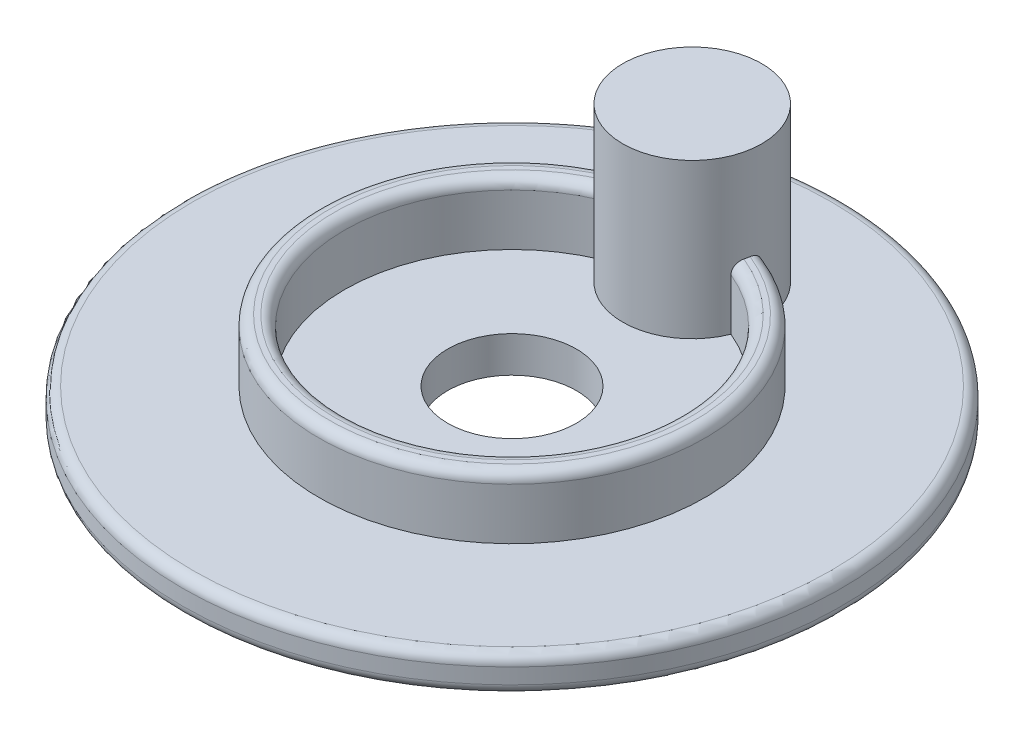
SolidWorks part; units mm, degrees
ref_plane "Front Plane" through (0, 0, 0) normal (0, 0, 1) x (1, 0, 0)
ref_plane "Top Plane" through (0, 0, 0) normal (0, 1, 0) x (1, 0, 0)
ref_plane "Right Plane" through (0, 0, 0) normal (1, 0, 0) x (0, 0, -1)
sketch "Sketch1" plane through (0, 0, 0) normal (0, 1, 0) x (1, 0, 0)
  circle A0 centre (0, 0) radius 64
  dimension "D1" = 128
extrude "Boss-Extrude1" add sketch "Sketch1" along normal blind 7
sketch "Sketch2" plane through (0, 7, 0) normal (0, 1, 0) x (1, 0, 0)
  circle A0 centre (0, 0) radius 37.5
  circle A1 centre (0, 0) radius 32.5
  dimension "D1" = 75
  dimension "D2" = 5
extrude "Boss-Extrude2" add sketch "Sketch2" along normal blind 12
sketch "Sketch3" plane through (0, 7, 0) normal (0, 1, 0) x (1, 0, 0)
  circle A0 centre (0, 0) radius 12.5
  dimension "D1" = 25
extrude "Cut-Extrude1" cut sketch "Sketch3" against normal through all
sketch "Sketch6" plane through (0, 7, 0) normal (0, 1, 0) x (1, 0, 0)
  point P0 (-2.1607, 23.1784)
  point P2 (0, -23.9641)
sketch "Sketch9" plane through (0, 7, 0) normal (0, 1, 0) x (1, 0, 0)
  point P0 (0, 23.7677)
  point P2 (0, -21.4106)
  point P5 (0, 23.7677)
  point P6 (0, -21.4106)
fillet "Fillet1" radius 2 4 edges at (0, 0, 64) (0, 7, 64) (0, 19, 32.5) (0, 19, 37.5)
sketch "Sketch17" plane through (0, 7, 0) normal (0, 1, 0) x (1, 0, 0)
  line L0 (0, 0) -> (0, 35) construction
  circle A0 centre (0, 35) radius 13.5
  dimension "D1" = 27
  dimension "D2" = 35
extrude "Boss-Extrude3" add sketch "Sketch17" along normal blind 30
